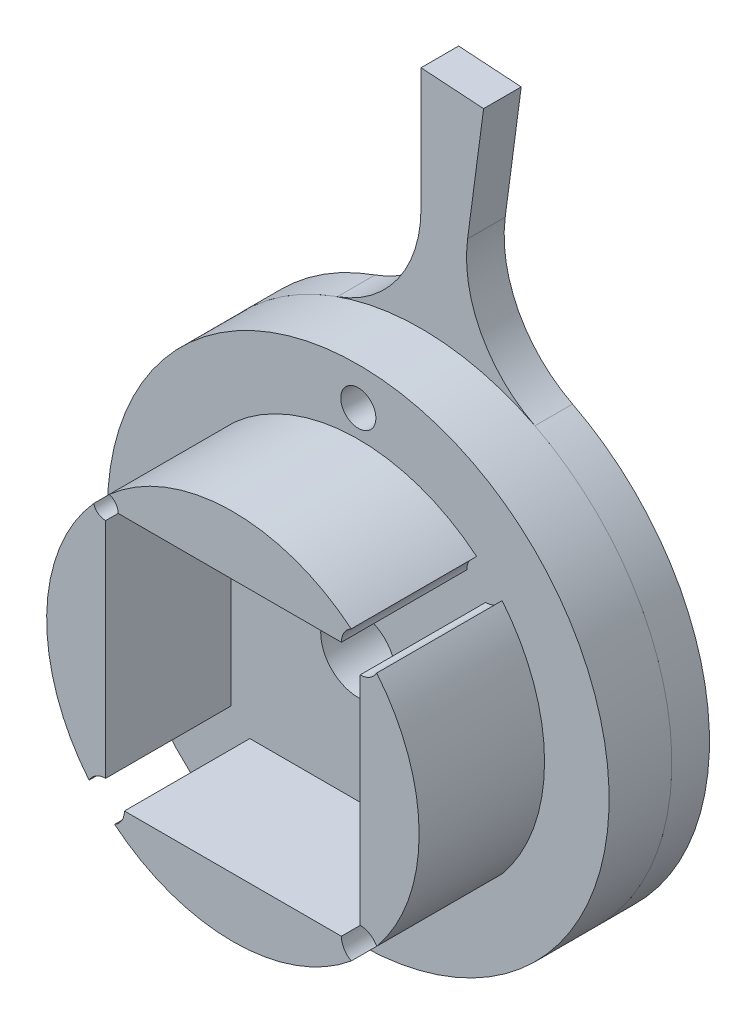
SolidWorks part; units mm, degrees
ref_plane "前视基准面" through (0, 0, 0) normal (0, 0, 1) x (1, 0, 0)
ref_plane "上视基准面" through (0, 0, 0) normal (0, 1, 0) x (1, 0, 0)
ref_plane "右视基准面" through (0, 0, 0) normal (1, 0, 0) x (0, 0, -1)
sketch "草图1" plane through (0, 0, 0) normal (0, 0, 1) x (1, 0, 0)
  line L1 (-10.15, 10.15) -> (10.15, 10.15)
  line L2 (-10.15, 10.15) -> (-10.15, -10.15)
  line L3 (-10.15, -10.15) -> (10.15, -10.15)
  line L4 (10.15, 10.15) -> (10.15, -10.15)
  line L5 (-10.15, 10.15) -> (10.15, -10.15) construction
  line L6 (-10.15, -10.15) -> (10.15, 10.15) construction
  circle A0 centre (0, 0) radius 14.85
  circle A1 centre (10.15, 10.15) radius 1.5
  circle A2 centre (10.15, -10.15) radius 1.5
  circle A3 centre (-10.15, -10.15) radius 1.5
  circle A4 centre (-10.15, 10.15) radius 1
  dimension "D1" = 29.7
  dimension "D4" = 3
  dimension "D5" = 3
  dimension "D6" = 3
  dimension "D7" = 2
  dimension "D2" = 20.3
  dimension "D3" = 20.3
extrude "凸台-拉伸1" add sketch "草图1" along normal blind 10 contours A4 L1 A1 A0 | A4 A0 A3 L2 | A2 A0 A1 L4 | A3 A0 A2 L3
sketch "草图3" plane through (0, 0, 0) normal (0, 0, -1) x (-1, 0, 0)
  circle A0 centre (0, 0) radius 3
  circle A1 centre (0, 0) radius 20
  dimension "D1" = 6
  dimension "D2" = 40
extrude "凸台-拉伸3" add sketch "草图3" along normal blind 5
sketch "草图4" plane through (0, 0, -5) normal (0, 0, -1) x (-1, 0, 0)
  circle A0 centre (0, 0) radius 3 construction
  circle A1 centre (0, 0) radius 20
  circle A2 centre (0, 0) radius 20
  circle A3 centre (0, 0) radius 3
  dimension "D1" = 0
extrude "凸台-拉伸4" add sketch "草图4" along normal blind 3
ref_plane "基准面1" through (0, 0, -5) normal (0, 0, -1) x (-1, 0, 0)
sketch "草图9" plane through (0, 0, -8) normal (0, 0, -1) x (-1, 0, 0)
  line L0 (0, 20) -> (0, 38)
  line L1 (0, 38) -> (-4.9892, 37.6711)
  line L2 (-2.4946, 37.8355) -> (-1.3158, 19.9567) construction
  line L3 (-2.6259, 19.8269) -> (-4.9892, 37.6711)
  circle A0 centre (0, 0) radius 20 construction
  arc A1 (0, 20) -> (-2.6259, 19.8269) centre (0, 0) ccw
  dimension "D1" = 38
  dimension "D2" = 5
extrude "凸台-拉伸7" add sketch "草图9" against normal blind 3
fillet "圆角2" radius 10 2 edges at (2.6259, 19.8269, -6.5) (0, 20, -6.5)
split "分割1" trim tools "基准面1" bodies to split 116 resulting bodies 109 110
sketch "草图5" plane through (0, 0, -8) normal (0, 0, -1) x (-1, 0, 0)
  circle A0 centre (0, 17) radius 1.4
  dimension "D1" = 2.8
  dimension "D2" = 17
extrude "切除-拉伸1" cut sketch "草图5" against normal blind 10
